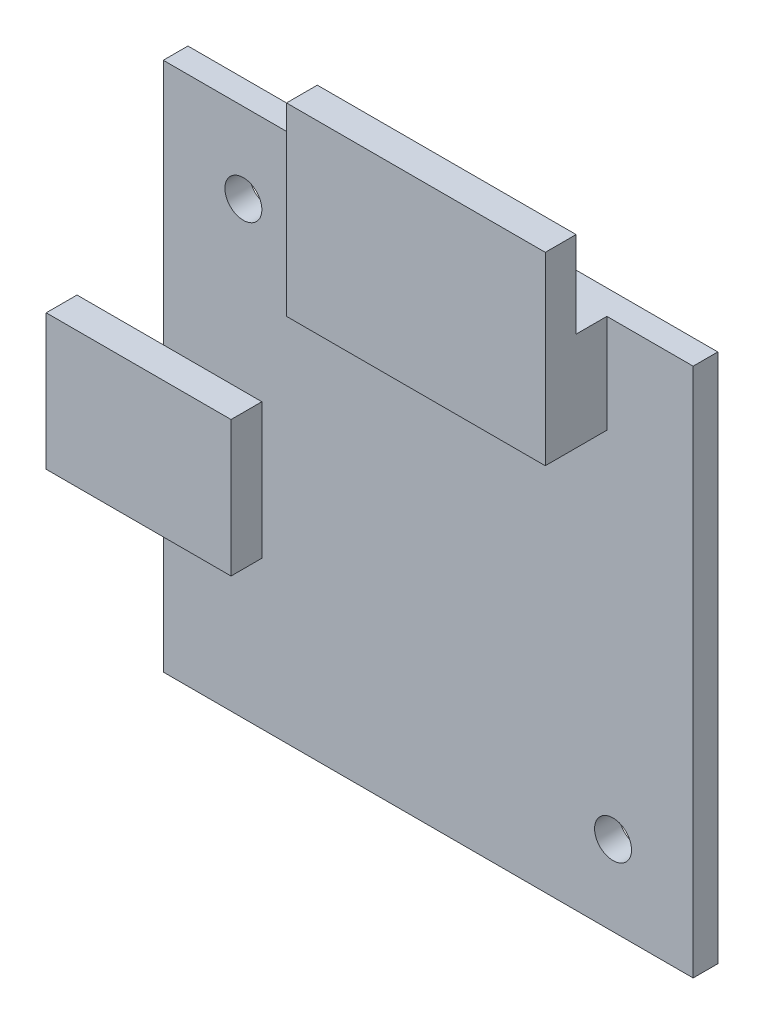
SolidWorks part; units mm, degrees
ref_plane "Front Plane" through (0, 0, 0) normal (0, 0, 1) x (1, 0, 0)
ref_plane "Top Plane" through (0, 0, 0) normal (0, 1, 0) x (1, 0, 0)
ref_plane "Right Plane" through (0, 0, 0) normal (1, 0, 0) x (0, 0, -1)
sketch "Sketch2" plane through (0, 0, 0) normal (0, 0, 1) x (1, 0, 0)
  line L1 (0, 0) -> (43, 0)
  line L2 (0, 0) -> (0, 43)
  line L3 (0, 43) -> (43, 43)
  line L4 (43, 0) -> (43, 43)
  dimension "D1" = 43
  dimension "D2" = 43
extrude "Boss-Extrude1" add sketch "Sketch2" along normal blind 2
sketch "Sketch3" plane through (0, 0, 2) normal (0, 0, 1) x (1, 0, 0)
  line L0 (43, 43) -> (0, 43) construction
  line L1 (0, 43) -> (0, 0) construction
  circle A0 centre (6.5, 36.5) radius 1.5
  dimension "D1" = 3
  dimension "D2" = 6.5
  dimension "D3" = 6.5
extrude "Cut-Extrude1" cut sketch "Sketch3" against normal up to next
sketch "Sketch4" plane through (0, 0, 2) normal (0, 0, 1) x (1, 0, 0)
  line L0 (0, 0) -> (43, 0) construction
  line L1 (43, 0) -> (43, 43) construction
  circle A0 centre (36.5, 6.5) radius 1.5
  dimension "D1" = 3
  dimension "D2" = 6.5
  dimension "D3" = 6.5
extrude "Cut-Extrude2" cut sketch "Sketch4" against normal up to next
sketch "Sketch5" plane through (0, 0, 2) normal (0, 0, 1) x (1, 0, 0)
  line L0 (0, 43) -> (0, 0) construction
  line L1 (15, 35) -> (36, 35)
  line L2 (15, 35) -> (15, 50)
  line L3 (15, 50) -> (36, 50)
  line L4 (36, 35) -> (36, 50)
  line L5 (43, 43) -> (0, 43) construction
  dimension "D1" = 21
  dimension "D2" = 15
  dimension "D3" = 15
  dimension "D4" = 8
extrude "Boss-Extrude2" add sketch "Sketch5" along normal blind 5
sketch "Sketch6" plane through (0, 0, 2) normal (0, 0, 1) x (1, 0, 0)
  line L0 (0, 43) -> (0, 0) construction
  line L1 (8, 12) -> (-7, 12)
  line L2 (8, 12) -> (8, 23)
  line L3 (8, 23) -> (-7, 23)
  line L4 (-7, 12) -> (-7, 23)
  line L5 (15, 43) -> (0, 43) construction
  dimension "D1" = 15
  dimension "D2" = 11
  dimension "D3" = 8
  dimension "D4" = 20
extrude "Boss-Extrude3" add sketch "Sketch6" along normal blind 2.5
sketch "Sketch7" plane through (0, 0, 2) normal (0, 0, -1) x (-1, 0, 0)
  line L0 (-15, 50) -> (-15, 43) construction
  line L1 (-36, 50) -> (-15, 50)
  line L2 (-36, 50) -> (-36, 43)
  line L3 (-36, 43) -> (-15, 43)
  line L4 (-15, 50) -> (-15, 43)
  line L5 (-15, 43) -> (0, 43) construction
extrude "Cut-Extrude3" cut sketch "Sketch7" against normal blind 2.5
